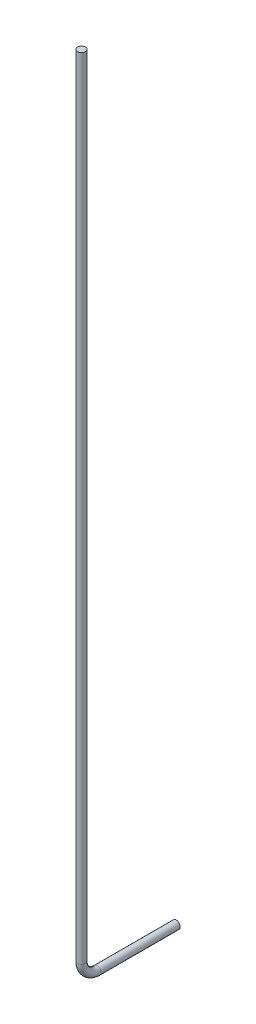
SolidWorks part; units mm, degrees
ref_plane "正面" through (0, 0, 0) normal (0, 0, 1) x (1, 0, 0)
ref_plane "平面" through (0, 0, 0) normal (0, 1, 0) x (1, 0, 0)
ref_plane "右側面" through (0, 0, 0) normal (1, 0, 0) x (0, 0, -1)
sketch "ｽｹｯﾁ1" plane through (0, 0, 0) normal (0, 0, 1) x (1, 0, 0)
  circle A0 centre (0, 0) radius 1.27
  dimension "D1" = 2.54
extrude "ﾎﾞｽ - 押し出し1" add sketch "ｽｹｯﾁ1" along normal blind 20
sketch "ｽｹｯﾁ2" plane through (0, 0, 20) normal (0, 0, 1) x (1, 0, 0)
  circle A1 centre (0, 0) radius 1.27
  circle A2 centre (0, 0) radius 1.27
  dimension "D1" = 0
sketch "ｽｹｯﾁ3" plane through (0, 0, 0) normal (1, 0, 0) x (0, 0, -1)
  line L0 (-20, 0) -> (-25, 0)
  line L1 (-20, 1.27) -> (-20, -1.27) construction
  line L2 (-30, 5) -> (-30, 255)
  line L3 (-20, 1.27) -> (-20, -1.27) construction
  arc A0 (-25, 0) -> (-30, 5) centre (-25, 5) cw
  point P8 (-30, 0)
  dimension "D2" = 5
  dimension "D1" = 10
  dimension "D3" = 250
sweep "ｽｲｰﾌﾟ1" add profiles "ｽｹｯﾁ2" path "ｽｹｯﾁ3"
